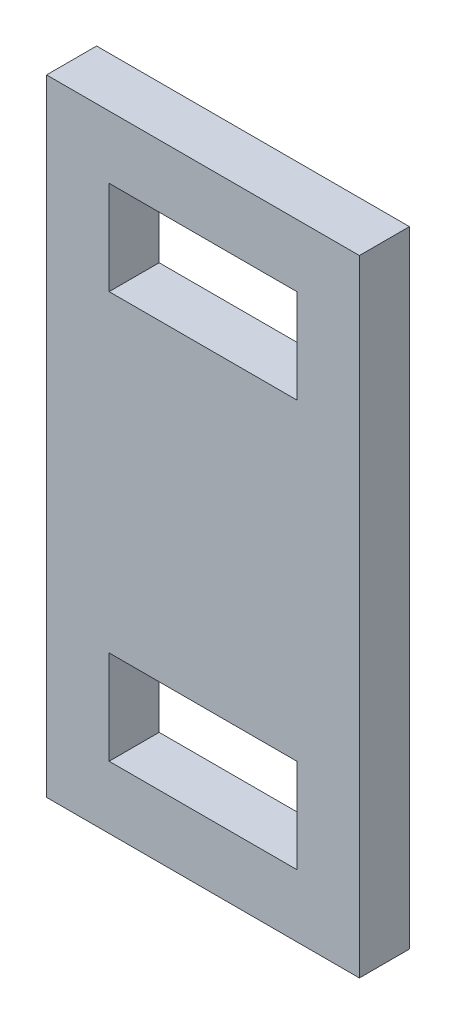
SolidWorks part; units mm, degrees
ref_plane "Plan de face" through (0, 0, 0) normal (0, 0, 1) x (1, 0, 0)
ref_plane "Plan de dessus" through (0, 0, 0) normal (0, 1, 0) x (1, 0, 0)
ref_plane "Plan de droite" through (0, 0, 0) normal (1, 0, 0) x (0, 0, -1)
sketch "Esquisse1" plane through (0, 0, 0) normal (0, 0, 1) x (1, 0, 0)
  line L0 (-1.5, -2.5) -> (-1.5, -4)
  line L1 (-2.5, 5) -> (2.5, 5)
  line L2 (-2.5, 5) -> (-2.5, -5)
  line L3 (-2.5, -5) -> (2.5, -5)
  line L4 (2.5, 5) -> (2.5, -5)
  line L5 (-1.5, 4) -> (1.5, 4)
  line L6 (-1.5, 4) -> (-1.5, 2.5)
  line L7 (-1.5, 2.5) -> (1.5, 2.5)
  line L8 (1.5, 4) -> (1.5, 2.5)
  line L9 (-1.5, -2.5) -> (1.5, -2.5)
  line L10 (1.5, -2.5) -> (1.5, -4)
  line L11 (-1.5, -4) -> (1.5, -4)
  dimension "D1" = 2.5
  dimension "D2" = 5
  dimension "D3" = 10
  dimension "D4" = 5
  dimension "D5" = 1.5
  dimension "D6" = 1
  dimension "D7" = 3
  dimension "D8" = 1
  dimension "D10" = 1
  dimension "D9" = 2
extrude "Boss.-Extru.1" add sketch "Esquisse1" along normal blind 0.8
